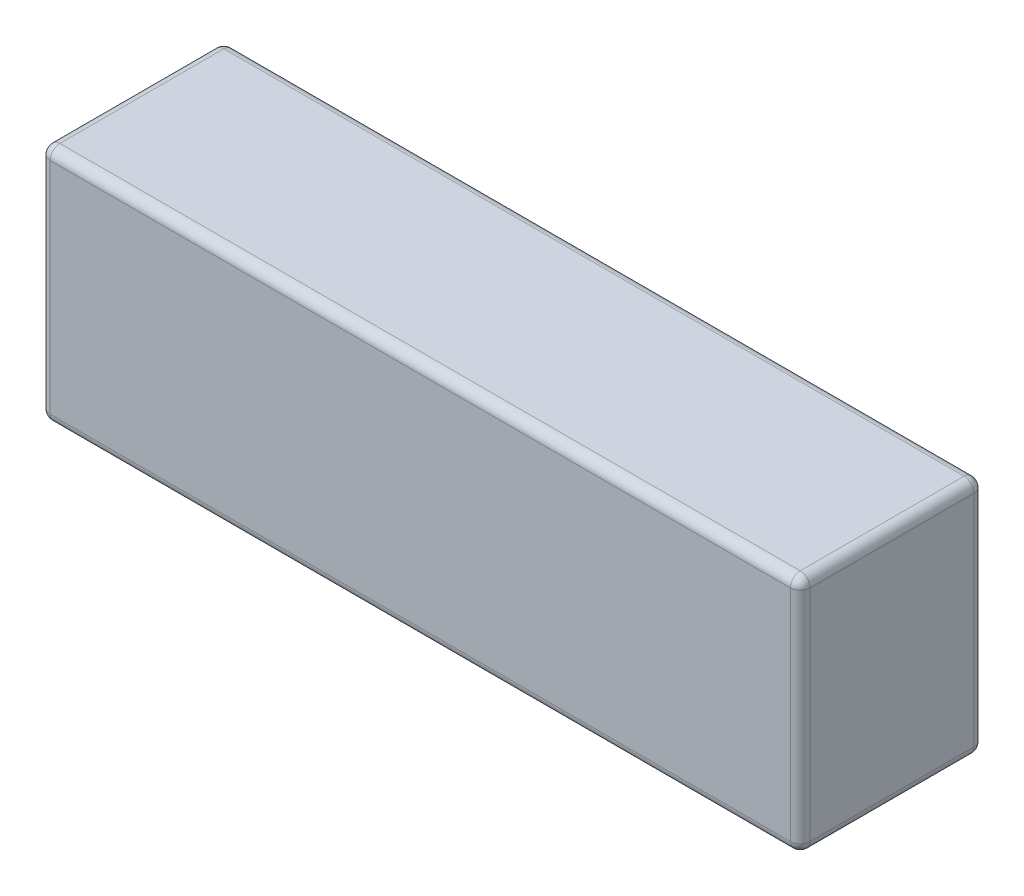
SolidWorks part; units mm, degrees
ref_plane "Front Plane" through (0, 0, 0) normal (0, 0, 1) x (1, 0, 0)
ref_plane "Top Plane" through (0, 0, 0) normal (0, 1, 0) x (1, 0, 0)
ref_plane "Right Plane" through (0, 0, 0) normal (1, 0, 0) x (0, 0, -1)
sketch "Sketch1" plane through (0, 0, 0) normal (0, 1, 0) x (1, 0, 0)
  line L1 (77, -18.6) -> (-77, -18.6)
  line L2 (77, -18.6) -> (77, 18.6)
  line L3 (77, 18.6) -> (-77, 18.6)
  line L4 (-77, -18.6) -> (-77, 18.6)
  line L5 (77, -18.6) -> (-77, 18.6) construction
  line L6 (77, 18.6) -> (-77, -18.6) construction
  point P0 (0, 0)
  dimension "D1" = 154
  dimension "D2" = 37.2
extrude "Boss-Extrude1" add sketch "Sketch1" along normal blind 48.5
fillet "Fillet1" radius 2 12 edges at (77, 0, 0) (-77, 0, 0) (77, 24.25, -18.6) (-77, 24.25, -18.6) (0, 0, -18.6) (0, 48.5, -18.6) (77, 48.5, 0) (-77, 48.5, 0) (-77, 24.25, 18.6) (0, 48.5, 18.6) (77, 24.25, 18.6) (0, 0, 18.6)
